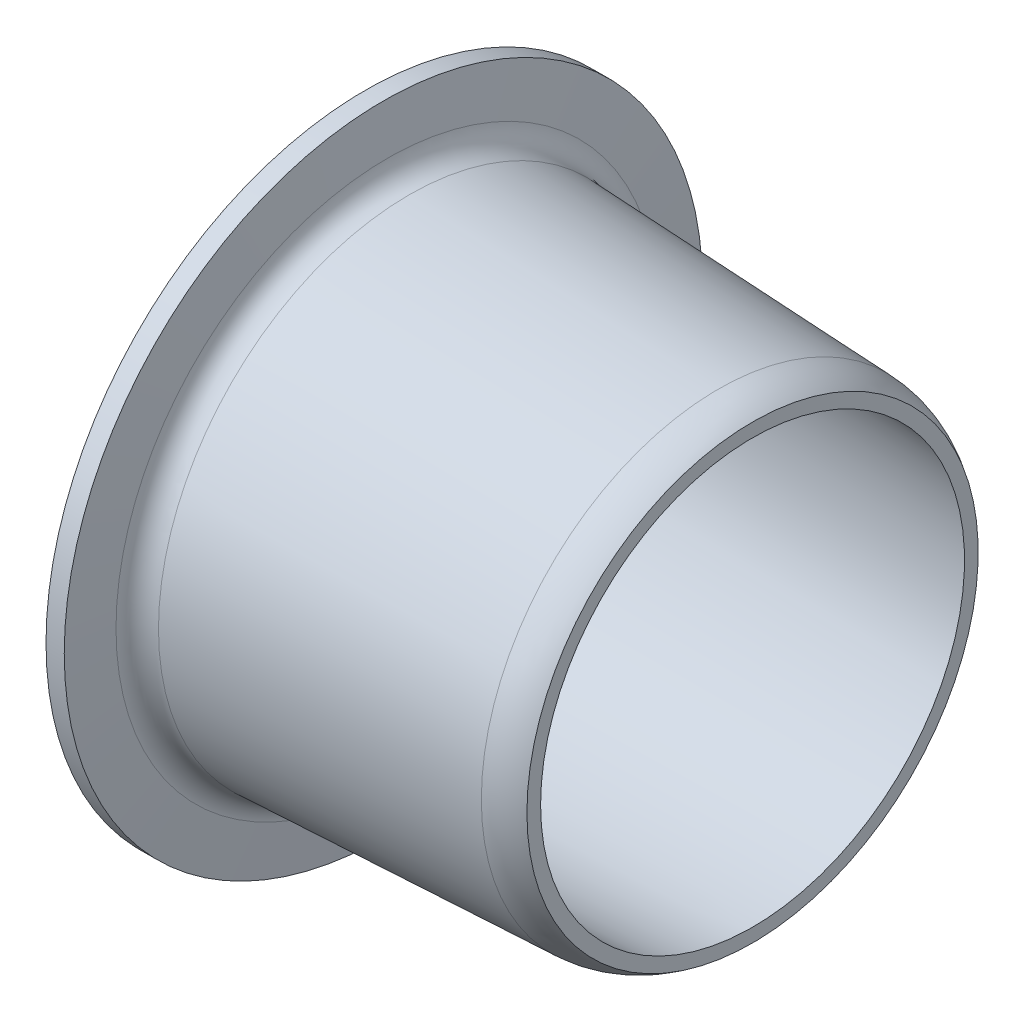
SolidWorks part; units mm, degrees
ref_plane "Plano frontal" through (0, 0, 0) normal (0, 0, 1) x (1, 0, 0)
ref_plane "Plano superior" through (0, 0, 0) normal (0, 1, 0) x (1, 0, 0)
ref_plane "Plano direito" through (0, 0, 0) normal (1, 0, 0) x (0, 0, -1)
sketch "Esboço1" plane through (0, 0, 0) normal (0, 0, 1) x (1, 0, 0)
  line L0 (0, 0) -> (3.8606, 0) construction
  line L1 (0, 2.1998) -> (0, 2.8)
  line L2 (0, 2.8) -> (0.16, 2.8)
  line L3 (0.16, 2.8) -> (0.1965, 2.3824)
  line L4 (0.3869, 2.2) -> (3.1, 2.08)
  line L5 (0.1913, 2) -> (3.4, 1.86)
  line L6 (3.4, 1.98) -> (3.4, 1.86)
  arc A0 (0.1965, 2.3824) -> (0.3869, 2.2) centre (0.3958, 2.3998) ccw
  arc A1 (3.1, 2.08) -> (3.4, 1.98) centre (3.0745, 1.5035) cw
  arc A2 (0.1913, 2) -> (0, 2.1998) centre (0.2, 2.1998) cw
  dimension "D4" = 4.4
  dimension "D2" = 0.2
  dimension "D9" = 0.2
  dimension "D1" = 5.6
  dimension "D3" = 0.16
  dimension "D5" = 4.16
  dimension "D6" = 3.4
  dimension "D7" = 5
  dimension "D8" = 4
  dimension "D10" = 2.498
  dimension "D11" = 0.3
  dimension "D12" = 0.12
  dimension "D13" = 3.72
revolve "Revolução1" add sketch "Esboço1" angle 360 about L0
fillet "Filete3" [suppressed] radius 0.05
